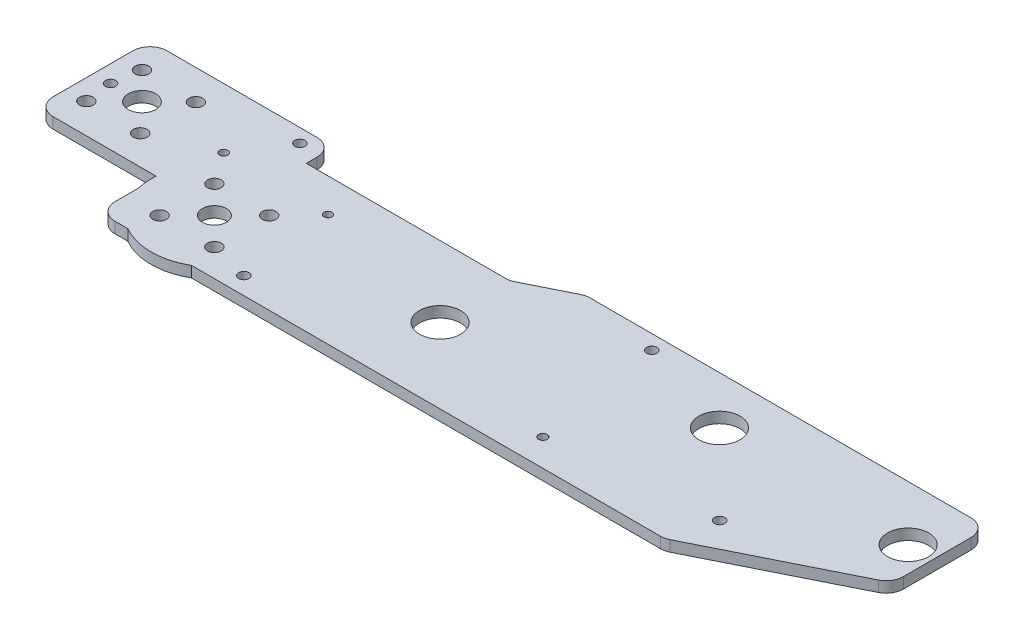
SolidWorks part; units mm, degrees
ref_plane "Front" through (0, 0, 0) normal (0, 0, 1) x (1, 0, 0)
ref_plane "Top" through (0, 0, 0) normal (0, 1, 0) x (1, 0, 0)
ref_plane "Right" through (0, 0, 0) normal (1, 0, 0) x (0, 0, -1)
sketch "Sketch1" plane through (0, 0, 0) normal (0, 1, 0) x (1, 0, 0)
  line L1 (0, 0) -> (210, 0)
  line L2 (0, 0) -> (0, -50)
  line L3 (0, -50) -> (210, -50)
  line L4 (210, 0) -> (210, -50)
  circle A7 centre (3.4895, -16.7877) radius 1.2117
  circle A8 centre (34.3726, -17.194) radius 1.1656
  circle A9 centre (37.5207, -44.9212) radius 1.5
  circle A10 centre (122, -42.0581) radius 1.25
  circle A12 centre (168.9752, -37.4032) radius 1.5173
  circle A13 centre (18, -34) radius 3.4
  dimension "D1" = 210
  dimension "D2" = 50
extrude "Boss-Extrude1" add sketch "Sketch1" along normal blind 3.175
sketch "Sketch2" plane through (0, 3.175, 0) normal (0, 1, 0) x (1, 0, 0)
  line L0 (210, 0) -> (0, 0) construction
  line L1 (0, 0) -> (0, -50) construction
  circle A0 centre (10, -26) radius 2
  circle A1 centre (10, -42) radius 2
  circle A2 centre (26, -26) radius 2
  circle A3 centre (26, -42) radius 2
  dimension "D1" = 16
  dimension "D2" = 16
  dimension "D3" = 16
  dimension "D4" = 26
  dimension "D5" = 10
  dimension "D6" = 10
  dimension "D7" = 26
  dimension "D8" = 16
extrude "Cut-Extrude1" cut sketch "Sketch2" against normal blind 10
sketch "Sketch3" plane through (0, 3.175, 0) normal (0, 1, 0) x (1, 0, 0)
  line L0 (210, 0) -> (0, 0) construction
  line L1 (210, 0) -> (0, 0) construction
  circle A0 centre (78.0103, -28.1) radius 6
  circle A1 centre (145.5313, -14) radius 6
  circle A2 centre (18, -34) radius 0.587
  circle A3 centre (26, -26) radius 2 construction
  circle A4 centre (202.6463, -16) radius 6
  dimension "D1" = 28.1
  dimension "D3" = 16
  dimension "D4" = 14
  dimension "D7" = 125.222
  dimension "D2" = 60.2996
  dimension "D5" = 8
  dimension "D6" = 8
  dimension "D8" = 57.15
extrude "Cut-Extrude2" cut sketch "Sketch3" against normal blind 57.15
sketch "Sketch4" [suppressed] plane through (0, 3.175, 0) normal (0, 1, 0) x (1, 0, 0)
  line L0 (3.4895, -16.7877) -> (18, -34)
  line L1 (3.4895, -20.6627) -> (5.9498, -23.5811)
  line L2 (18, -34) -> (34.3726, -17.194)
  line L3 (34.3726, -17.194) -> (75.8499, -28.1)
  line L4 (75.8499, -28.1) -> (37.5207, -44.9212)
  line L5 (7.3432, -17.194) -> (9.8664, -20.303)
  circle A0 centre (18, -34) radius 15.9299
  circle A1 centre (3.4895, -16.7877) radius 3.8751
  circle A2 centre (34.3726, -17.194) radius 3.7227
  circle A3 centre (37.5207, -44.9212) radius 3.8676
  circle A4 centre (75.8499, -28.1) radius 12.797
  circle A5 centre (112.3021, -4.7393) radius 5.1588
  circle A6 centre (118.879, -40.0177) radius 4.9035
  circle A7 centre (140.772, -16) radius 12.6375
  circle A8 centre (168.9752, -37.4032) radius 4.2066
  circle A9 centre (197.922, -16) radius 12.8
sketch "Sketch5" [suppressed] plane through (0, 3.175, 0) normal (0, 1, 0) x (1, 0, 0)
  line L0 (210, 0) -> (0, 0) construction
  line L2 (-0.6266, -16.7877) -> (37.5207, -16.7877)
  line L3 (-0.6266, -16.7877) -> (-0.6266, -44.9212)
  line L4 (-0.6266, -44.9212) -> (37.5207, -44.9212)
  line L5 (37.5207, -16.7877) -> (37.5207, -44.9212)
  line L6 (75.8499, -15.182) -> (37.5207, -15.182)
  line L7 (75.8499, -15.182) -> (75.8499, -44.9212)
  line L8 (75.8499, -44.9212) -> (37.5207, -44.9212)
  line L9 (37.5207, -15.182) -> (37.5207, -44.9212)
  line L10 (112.3021, -4.7393) -> (75.8499, -4.7393)
  line L11 (112.3021, -4.7393) -> (112.3021, -44.9212)
  line L12 (112.3021, -44.9212) -> (75.8499, -44.9212)
  line L13 (75.8499, -4.7393) -> (75.8499, -44.9212)
  line L14 (112.3021, -4.7393) -> (102.3945, -4.7393)
  line L16 (112.3021, -4.7393) -> (112.3021, 0)
  line L17 (112.3021, 0) -> (102.3945, 0)
  line L18 (102.3945, -4.7393) -> (102.3945, 0)
  line L19 (210, -50) -> (210, 0) construction
  line L20 (112.3021, -4.7393) -> (123.1553, -4.7393)
  line L21 (112.3021, -4.7393) -> (112.3021, 0)
  line L22 (112.3021, 0) -> (123.1553, 0)
  line L23 (123.1553, -4.7393) -> (123.1553, 0)
  line L24 (112.3021, -4.7393) -> (140.772, -4.7393)
  line L25 (112.3021, -4.7393) -> (112.3021, -40.0177)
  line L26 (112.3021, -40.0177) -> (140.772, -40.0177)
  line L27 (140.772, -4.7393) -> (140.772, -40.0177)
  line L28 (140.772, -16) -> (168.9752, -16)
  line L29 (140.772, -16) -> (140.772, -40.0177)
  line L30 (140.772, -40.0177) -> (168.9752, -40.0177)
  line L31 (168.9752, -16) -> (168.9752, -40.0177)
  line L32 (168.9752, -4.7393) -> (210, -4.7393)
  line L33 (168.9752, -4.7393) -> (168.9752, -40.0177)
  line L34 (168.9752, -40.0177) -> (210, -40.0177)
  line L35 (210, -4.7393) -> (210, -40.0177)
  line L36 (0, -50) -> (210, -50) construction
  line L37 (160.7629, -40.0177) -> (177.2091, -40.0177)
  line L38 (160.7629, -40.0177) -> (160.7629, -44.9212)
  line L39 (160.7629, -44.9212) -> (177.2091, -44.9212)
  line L40 (177.2091, -40.0177) -> (177.2091, -44.9212)
  line L41 (112.3021, -40.0177) -> (126.3591, -40.0177)
  line L42 (112.3021, -40.0177) -> (112.3021, -47.7828)
  line L43 (112.3021, -47.7828) -> (126.3591, -47.7828)
  line L44 (126.3591, -40.0177) -> (126.3591, -47.7828)
  line L45 (30.5963, -44.9212) -> (44.6115, -44.9212)
  line L46 (30.5963, -44.9212) -> (30.5963, -50)
  line L47 (30.5963, -50) -> (44.6115, -50)
  line L48 (44.6115, -44.9212) -> (44.6115, -50)
  line L50 (-0.6266, -44.9212) -> (30.5963, -44.9212)
  line L51 (-0.6266, -44.9212) -> (-0.6266, -50)
  line L52 (-0.6266, -50) -> (30.5963, -50)
  line L53 (30.5963, -44.9212) -> (30.5963, -50)
  circle A0 centre (3.4895, -16.7877) radius 4.1161
  circle A1 centre (34.3726, -17.194) radius 3.8132
  circle A2 centre (75.8499, -28.1) radius 12.918
  circle A3 centre (112.3021, -4.7393) radius 5.2663
  circle A4 centre (140.772, -16) radius 13.0245
  circle A5 centre (197.922, -16) radius 12.3805
  circle A6 centre (168.9752, -37.4032) radius 4.7643
  circle A7 centre (118.879, -40.0177) radius 5.279
  circle A8 centre (37.5207, -44.9212) radius 4.2049
  line M12 (0, 0) -> (0, -50)
  line M13 (0, -50) -> (210, -50)
  line M14 (210, -50) -> (210, 0)
  line M15 (210, 0) -> (0, 0)
extrude "Cut-Extrude5" [suppressed] cut sketch "Sketch5" against normal blind 11.52 contours A5 L32 L23 L24 A4 L28 L33 M14 M15 | A1 L6 L13 L10 L18 A0 L2 M15 M12 | L8 L48 L34 L40 L39 L38 L30 L26 L44 L43 L42 L12 M13 M14
fillet "Fillet1" [suppressed] radius 5
sketch "Sketch10" plane through (0, 3.175, 0) normal (0, 1, 0) x (1, 0, 0)
  line L0 (210, -27.8594) -> (165.5029, -50)
  line L1 (210, -50) -> (210, 0) construction
  line L2 (0, -50) -> (210, -50) construction
  line L3 (165.5029, -50) -> (210, -50)
  line L4 (210, -50) -> (210, -27.8594)
  line L5 (92.5326, 0) -> (77.6548, -7.4028)
  line L6 (210, 0) -> (0, 0) construction
  line L7 (77.6548, -7.4028) -> (0, -7.4028)
  line L8 (0, 0) -> (0, -50) construction
  line L9 (0, -7.4028) -> (0, 0)
  line L10 (0, 0) -> (92.5326, 0)
extrude "Cut-Extrude7" cut sketch "Sketch10" against normal blind 10
fillet "Fillet3" radius 5 5 edges at (77.6548, 1.5875, 7.4028) (92.5326, 1.5875, 0) (210, 1.5875, 0) (210, 1.5875, 27.8594) (165.5029, 1.5875, 50)
sketch "Sketch11" plane through (0, 3.175, 0) normal (0, 1, 0) x (1, 0, 0)
  circle A0 centre (18, -34) radius 18.5
  circle A1 centre (10, -26) radius 2
  circle A2 centre (10, -42) radius 2
  circle A3 centre (26, -26) radius 2
  circle A4 centre (26, -42) radius 2
extrude "Boss-Extrude4" add sketch "Sketch11" against normal blind 3.175
sketch "Sketch16" plane through (0, 0, 7.4028) normal (0, 0, -1) x (-1, 0, 0)
  line L0 (0, 3.175) -> (-76.4796, 3.175) construction
  line L1 (0, 0) -> (-18.2576, 0)
  line L2 (0, 0) -> (0, 3.175)
  line L3 (0, 3.175) -> (-18.2576, 3.175)
  line L4 (-18.2576, 0) -> (-18.2576, 3.175)
extrude "Boss-Extrude7" add sketch "Sketch16" along normal blind 8.128
sketch "Sketch17" plane through (0, 0, 0) normal (-1, 0, 0) x (0, 0, 1)
  line L0 (-0.7252, 3.175) -> (29.728, 3.175) construction
  line L1 (-0.7252, 0) -> (32.5748, 0)
  line L2 (-0.7252, 0) -> (-0.7252, 3.175)
  line L3 (-0.7252, 3.175) -> (32.5748, 3.175)
  line L4 (32.5748, 0) -> (32.5748, 3.175)
  dimension "D1" = 33.3
extrude "Boss-Extrude8" add sketch "Sketch17" along normal blind 35.56
sketch "Sketch18" plane through (0, 3.175, 0) normal (0, 1, 0) x (1, 0, 0)
  line L0 (-35.56, 0.7252) -> (18.2576, 0.7252) construction
  circle A0 centre (-21.4859, -15.9248) radius 11.315
  circle A1 centre (-29.612, -23.7985) radius 2
  circle A2 centre (-29.3597, -7.7987) radius 2
  circle A3 centre (-13.3598, -8.0511) radius 2
  circle A4 centre (-13.6122, -24.0509) radius 2
  circle A5 centre (-21.4859, -15.9248) radius 4
  point P15 (-21.4859, -15.9248)
  dimension "D1" = 22.63
  dimension "D3" = 4
  dimension "D2" = 16.65
extrude "Cut-Extrude8" cut sketch "Sketch18" against normal blind 9 contours A2 | A1 | A4 | A3
sketch "Sketch19" plane through (0, 3.175, 0) normal (0, 1, 0) x (1, 0, 0)
  circle A0 centre (-21.3597, -15.7987) radius 4
  circle A1 centre (-29.3597, -7.7987) radius 2 construction
  dimension "D1" = 8
  dimension "D2" = 8
extrude "Cut-Extrude9" cut sketch "Sketch19" against normal blind 40
fillet "Fillet4" radius 5 4 edges at (0, 1.5875, 50) (18.2576, 1.5875, -0.7252) (-35.56, 1.5875, -0.7252) (-35.56, 1.5875, 32.5748)
sketch "Sketch20" plane through (0, 3.175, 0) normal (0, 1, 0) x (1, 0, 0)
  circle A0 centre (18, -34) radius 3.5
  circle A1 centre (10, -26) radius 2 construction
  dimension "D1" = 8
  dimension "D2" = 8
extrude "Cut-Extrude10" cut sketch "Sketch20" against normal blind 10
sketch "Sketch21" plane through (0, 3.175, 0) normal (0, 1, 0) x (1, 0, 0)
  line L0 (210, -24.7625) -> (210, -5) construction
  circle A0 centre (116, -4.2372) radius 1.5
  dimension "D1" = 94
extrude "Cut-Extrude11" cut sketch "Sketch21" against normal blind 10
sketch "Sketch22" plane through (0, 3.175, 0) normal (0, 1, 0) x (1, 0, 0)
  line L0 (18.2576, -4.2748) -> (18.2576, -7.4028) construction
  line L1 (-30.56, 0.7252) -> (13.2576, 0.7252) construction
  circle A0 centre (12.2576, -3.2748) radius 1.5
  dimension "D1" = 6
  dimension "D2" = 4
extrude "Cut-Extrude12" cut sketch "Sketch22" against normal blind 10
sketch "Sketch24" plane through (0, 3.175, 0) normal (0, 1, 0) x (1, 0, 0)
  line L0 (-30.56, 0.7252) -> (13.2576, 0.7252) construction
  line L1 (-35.56, -27.5748) -> (-35.56, -4.2748) construction
  circle A0 centre (-30.56, -15.7748) radius 1.5
  dimension "D1" = 16.5
  dimension "D2" = 5
extrude "Cut-Extrude13" cut sketch "Sketch24" against normal blind 10
